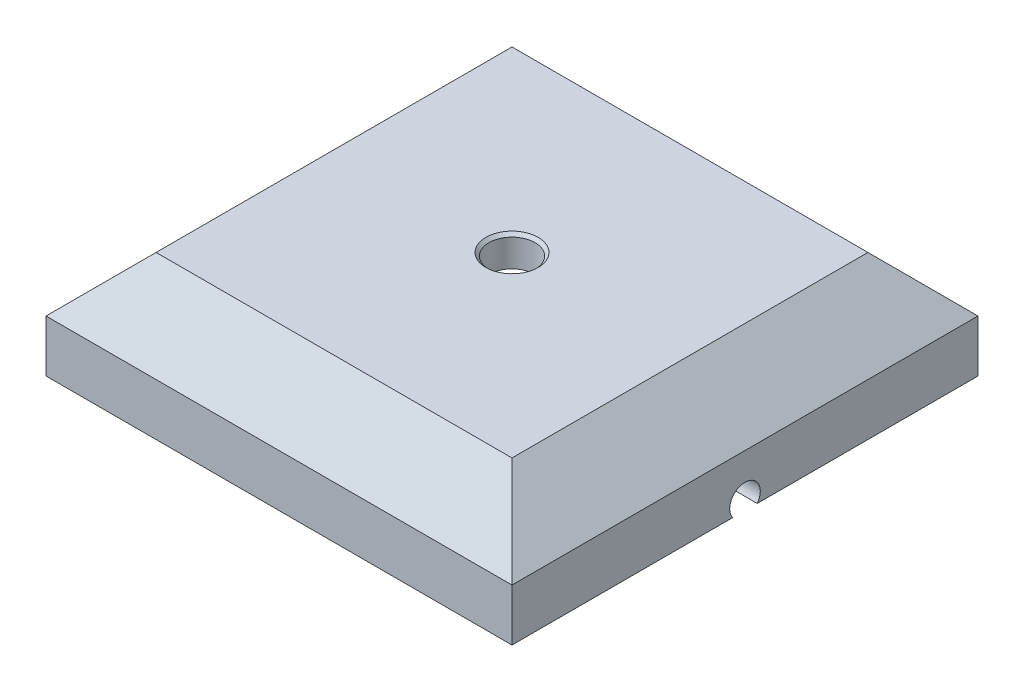
SolidWorks part; units mm, degrees
ref_plane "Front Plane" through (0, 0, 0) normal (0, 0, 1) x (1, 0, 0)
ref_plane "Top Plane" through (0, 0, 0) normal (0, 1, 0) x (1, 0, 0)
ref_plane "Right Plane" through (0, 0, 0) normal (1, 0, 0) x (0, 0, -1)
sketch "Sketch1" plane through (0, 0, 0) normal (0, 1, 0) x (1, 0, 0)
  line L1 (76.2, -76.2) -> (-76.2, -76.2)
  line L2 (76.2, -76.2) -> (76.2, 76.2)
  line L3 (76.2, 76.2) -> (-76.2, 76.2)
  line L4 (-76.2, -76.2) -> (-76.2, 76.2)
  line L5 (76.2, -76.2) -> (-76.2, 76.2) construction
  line L6 (76.2, 76.2) -> (-76.2, -76.2) construction
  point P0 (0, 0)
  dimension "D1" = 152.4
  dimension "D2" = 152.4
extrude "Boss-Extrude1" add sketch "Sketch1" along normal blind 35
sketch "Sketch2" plane through (0, 35, 0) normal (0, 1, 0) x (1, 0, 0)
  circle A0 centre (0, 0) radius 7.55
  dimension "D1" = 15.1
extrude "Cut-Extrude1" cut sketch "Sketch2" against normal through all
chamfer "Chamfer1" distance 18 angle 45 4 edges at (-76.2, 35, 0) (0, 35, -76.2) (76.2, 35, 0) (0, 35, 76.2)
sketch "Sketch3" plane through (0, 0, 0) normal (0, -1, 0) x (1, 0, 0)
  line L0 (0, 4.5) -> (0, -4.5) construction
  line L1 (1.5, 4.5) -> (1.5, -4.5)
  line L2 (-1.5, 4.5) -> (-1.5, -4.5)
  arc A0 (1.5, 4.5) -> (-1.5, 4.5) centre (0, 4.5) ccw
  arc A1 (-1.5, -4.5) -> (1.5, -4.5) centre (0, -4.5) ccw
  point P3 (0, 0)
  dimension "D1" = 12
  dimension "D2" = 3
sketch "Sketch4" plane through (76.2, 0, 0) normal (1, 0, 0) x (0, 0, -1)
  line L0 (0, 0) -> (0, 3) construction
  line L1 (-4.5, 0) -> (4.5, 0) construction
  circle A0 centre (0, 3) radius 5
  dimension "D1" = 10
  dimension "D2" = 3
extrude "Cut-Extrude2" cut sketch "Sketch4" against normal up to next
sketch "Sketch5" plane through (0, 0, 0) normal (0, -1, 0) x (1, 0, 0)
  line L0 (-76.2, 76.2) -> (-58.2, 58.2) construction
  line L1 (63.5, -63.5) -> (-63.5, -63.5)
  line L2 (63.5, -63.5) -> (63.5, 63.5)
  line L3 (63.5, 63.5) -> (-63.5, 63.5)
  line L4 (-63.5, -63.5) -> (-63.5, 63.5)
  line L5 (63.5, -63.5) -> (-63.5, 63.5) construction
  line L6 (63.5, 63.5) -> (-63.5, -63.5) construction
  point P0 (0, 0)
  dimension "D1" = 127
extrude "Cut-Extrude3" cut sketch "Sketch5" against normal blind 25
chamfer "Chamfer3" distance 1 angle 45 1 edges at (0, 35, 7.55)
